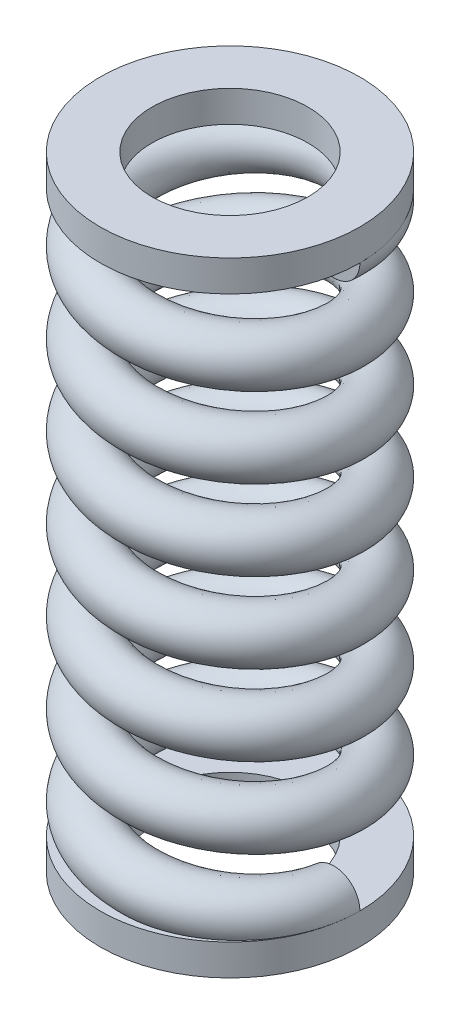
SolidWorks part; units mm, degrees
material "AISI 304"
ref_plane "Front Plane" through (0, 0, 0) normal (0, 0, 1) x (1, 0, 0)
ref_plane "Top Plane" through (0, 0, 0) normal (0, 1, 0) x (1, 0, 0)
ref_plane "Right Plane" through (0, 0, 0) normal (1, 0, 0) x (0, 0, -1)
sketch "Sketch1" plane through (0, 0, 0) normal (0, 1, 0) x (1, 0, 0)
  circle A0 centre (0, 0) radius 5
  dimension "D1" = 10
curve "Helix/Spiral1" pitch 3.8571 height 27 turns 7
sketch "Sketch2" plane through (0, 0, 0) normal (0, 0, 1) x (1, 0, 0)
  circle A0 centre (5, 0) radius 1.25
  spline S0 degree 3 poles (5, 0) (5, 0.0798) (4.7397, 0.2413) (3.6276, 0.4821) (1.9632, 0.7232) (0, 0.9643) (-1.9632, 1.2054) (-3.6276, 1.4464) (-4.7397, 1.6875) (-5.1302, 1.9286) (-4.7397, 2.1696) (-3.6276, 2.4107) (-1.4084, 2.7321) (1.4084, 3.0536) (3.6276, 3.375) (4.7397, 3.6161) (5.1302, 3.8571) (4.7397, 4.0982) (3.6276, 4.3393) (1.4084, 4.6607) (-1.4084, 4.9821) (-3.6276, 5.3036) (-4.7397, 5.5446) (-5.1302, 5.7857) (-4.7397, 6.0268) (-3.6276, 6.2679) (-1.4084, 6.5893) (1.4084, 6.9107) (3.6276, 7.2321) (4.7397, 7.4732) (5.1302, 7.7143) (4.7397, 7.9554) (3.6276, 8.1964) (1.4084, 8.5179) (-1.4084, 8.8393) (-3.6276, 9.1607) (-4.7397, 9.4018) (-5.1302, 9.6429) (-4.7397, 9.8839) (-3.6276, 10.125) (-1.4084, 10.4464) (1.4084, 10.7679) (3.6276, 11.0893) (4.7397, 11.3304) (5.1302, 11.5714) (4.7397, 11.8125) (3.6276, 12.0536) (1.4084, 12.375) (-1.4084, 12.6964) (-3.6276, 13.0179) (-4.7397, 13.2589) (-5.1302, 13.5) (-4.7397, 13.7411) (-3.6276, 13.9821) (-1.4084, 14.3036) (1.4084, 14.625) (3.6276, 14.9464) (4.7397, 15.1875) (5.1302, 15.4286) (4.7397, 15.6696) (3.6276, 15.9107) (1.4084, 16.2321) (-1.4084, 16.5536) (-3.6276, 16.875) (-4.7397, 17.1161) (-5.1302, 17.3571) (-4.7397, 17.5982) (-3.6276, 17.8393) (-1.4084, 18.1607) (1.4084, 18.4821) (3.6276, 18.8036) (4.7397, 19.0446) (5.1302, 19.2857) (4.7397, 19.5268) (3.6276, 19.7679) (1.4084, 20.0893) (-1.4084, 20.4107) (-3.6276, 20.7321) (-4.7397, 20.9732) (-5.1302, 21.2143) (-4.7397, 21.4554) (-3.6276, 21.6964) (-1.4084, 22.0179) (1.4084, 22.3393) (3.6276, 22.6607) (4.7397, 22.9018) (5.1302, 23.1429) (4.7397, 23.3839) (3.6276, 23.625) (1.4084, 23.9464) (-1.4084, 24.2679) (-3.6276, 24.5893) (-4.7397, 24.8304) (-5.1302, 25.0714) (-4.7397, 25.3125) (-3.6276, 25.5536) (-1.9632, 25.7946) (0, 26.0357) (1.9632, 26.2768) (3.6276, 26.5179) (4.7397, 26.7587) (5, 26.9202) (5, 27) knots 0 0 0 0 0.008929 0.017857 0.026786 0.035714 0.044643 0.053571 0.0625 0.071429 0.080357 0.089286 0.098214 0.116071 0.125 0.133929 0.142857 0.151786 0.160714 0.169643 0.1875 0.196429 0.205357 0.214286 0.223214 0.232143 0.241071 0.258929 0.267857 0.276786 0.285714 0.294643 0.303571 0.3125 0.330357 0.339286 0.348214 0.357143 0.366071 0.375 0.383929 0.401786 0.410714 0.419643 0.428571 0.4375 0.446429 0.455357 0.473214 0.482143 0.491071 0.5 0.508929 0.517857 0.526786 0.544643 0.553571 0.5625 0.571429 0.580357 0.589286 0.598214 0.616071 0.625 0.633929 0.642857 0.651786 0.660714 0.669643 0.6875 0.696429 0.705357 0.714286 0.723214 0.732143 0.741071 0.758929 0.767857 0.776786 0.785714 0.794643 0.803571 0.8125 0.830357 0.839286 0.848214 0.857143 0.866071 0.875 0.883929 0.901786 0.910714 0.919643 0.928571 0.9375 0.946429 0.955357 0.964286 0.973214 0.982143 0.991071 1 1 1 1 construction
  dimension "D1" = 2.5
sweep "Sweep1" add profiles "Sketch2" path "Helix/Spiral1"
sketch "Sketch3" plane through (0, 0, 0) normal (0, 1, 0) x (1, 0, 0)
  circle A0 centre (0, 0) radius 6.25
  circle A1 centre (0, 0) radius 3.75
  dimension "D1" = 12.5
  dimension "D2" = 7.5
extrude "Boss-Extrude1" add sketch "Sketch3" against normal blind 1.5
ref_plane "Plane1" through (0, 13.5, 0) normal (0, 1, 0) x (1, 0, 0)
mirror "Mirror1" about plane through (0, 13.5, 0) normal (0, 1, 0) of "Boss-Extrude1"
